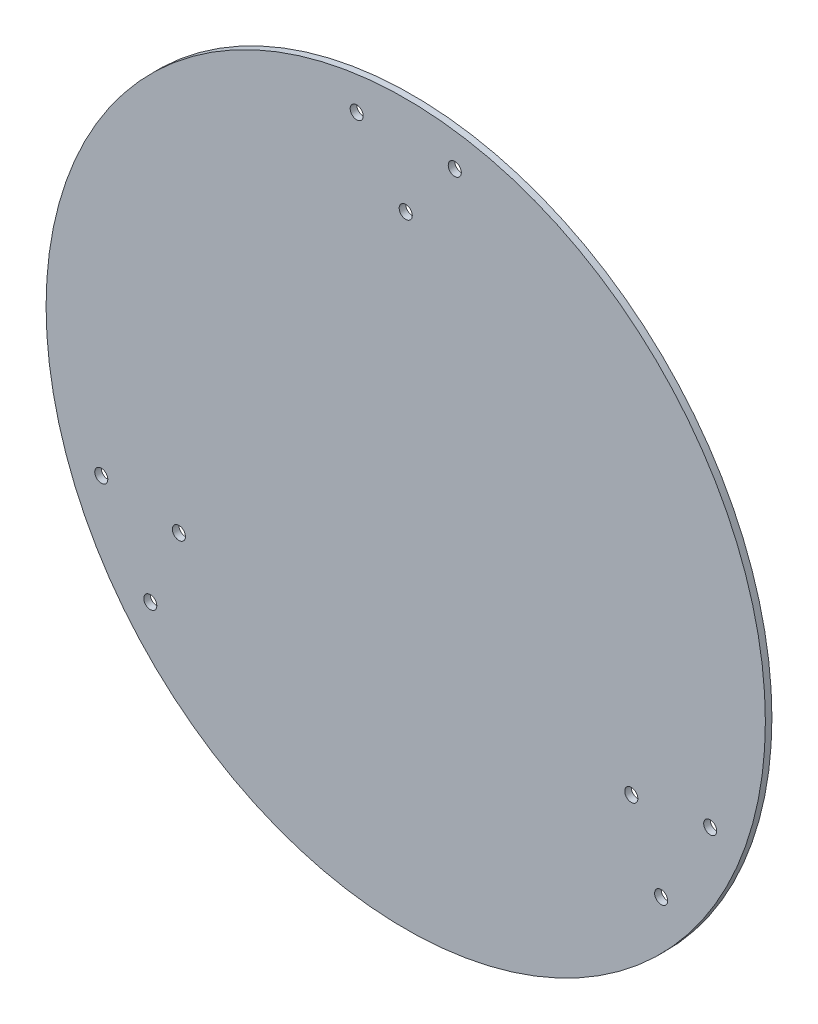
SolidWorks part; units mm, degrees
ref_plane "Plan de face" through (0, 0, 0) normal (0, 0, 1) x (1, 0, 0)
ref_plane "Plan de dessus" through (0, 0, 0) normal (0, 1, 0) x (1, 0, 0)
ref_plane "Plan de droite" through (0, 0, 0) normal (1, 0, 0) x (0, 0, -1)
sketch "Esquisse2" plane through (0, 0, 0) normal (0, 0, 1) x (1, 0, 0)
  circle A0 centre (0, 0) radius 110
  dimension "D1" = 220
extrude "Boss.-Extru.1" add sketch "Esquisse2" along normal blind 2
sketch "Esquisse7" plane through (0, 0, 0) normal (0, 0, -1) x (-1, 0, 0)
  line L0 (0, 110) -> (0, 0) construction
  line L1 (95.2628, -55) -> (0, 0) construction
  line L2 (-95.2628, -55) -> (0, 0) construction
  circle A0 centre (-15, 98.8686) radius 2
  circle A1 centre (15, 98.8686) radius 1.9911
  circle A2 centre (0, 0) radius 100 construction
  circle A3 centre (0, 0) radius 110 construction
  circle A4 centre (69.3771, -39.7184) radius 2
  circle A5 centre (93.1227, -36.4439) radius 2
  circle A6 centre (78.1227, -62.4247) radius 1.9911
  circle A7 centre (-68.9907, -39.9415) radius 2
  circle A8 centre (-78.1227, -62.4247) radius 2
  circle A9 centre (-93.1227, -36.4439) radius 1.9911
  circle A10 centre (0, 0) radius 80 construction
  circle A11 centre (0, 80) radius 2
  point P23 (0, 0)
  point P26 (0.1288, 0.1134)
  dimension "D1" = 4
  dimension "D2" = 160
  dimension "D3" = 4
extrude "Enlèv. mat.-Extru.7" cut sketch "Esquisse7" against normal blind 2
sketch "Esquisse8" plane through (0, 0, 0) normal (0, 0, -1) x (-1, 0, 0)
  line L0 (0, 0) -> (2, 80) construction
  line L1 (0, 0) -> (69.3771, -39.7184) construction
  line L2 (0, 0) -> (-68.9907, -39.9415) construction
  circle A1 centre (0, 80) radius 2 construction
